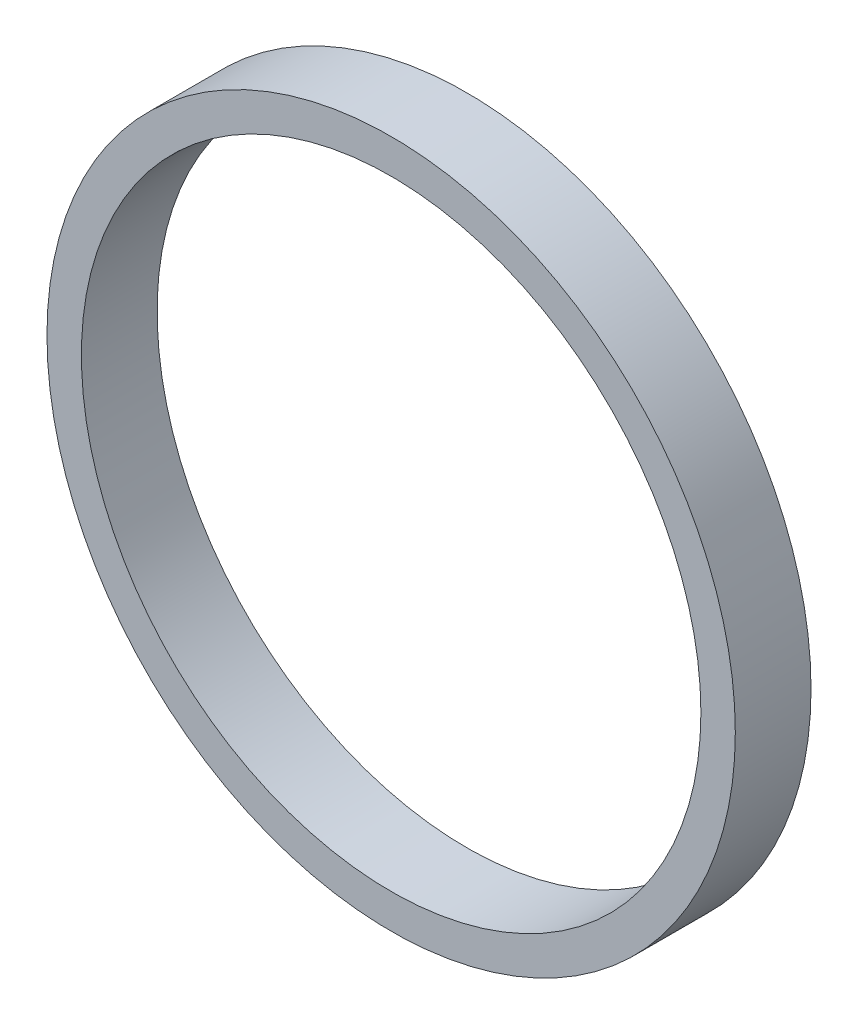
SolidWorks part; units mm, degrees
ref_plane "Ebene vorne" through (0, 0, 0) normal (0, 0, 1) x (1, 0, 0)
ref_plane "Ebene oben" through (0, 0, 0) normal (0, 1, 0) x (1, 0, 0)
ref_plane "Ebene rechts" through (0, 0, 0) normal (1, 0, 0) x (0, 0, -1)
sketch "Skizze1" plane through (0, 0, 0) normal (0, 0, 1) x (1, 0, 0)
  circle A0 centre (0, 0) radius 50
  dimension "D1" = 100
extrude "Aufsatz-Linear austragen1" add sketch "Skizze1" along normal blind 11
sketch "Skizze2" plane through (0, 0, 11) normal (0, 0, 1) x (1, 0, 0)
  circle A0 centre (0, 0) radius 45
  dimension "D1" = 90
extrude "Schnitt-Linear austragen1" cut sketch "Skizze2" against normal through all both and the other way through all
